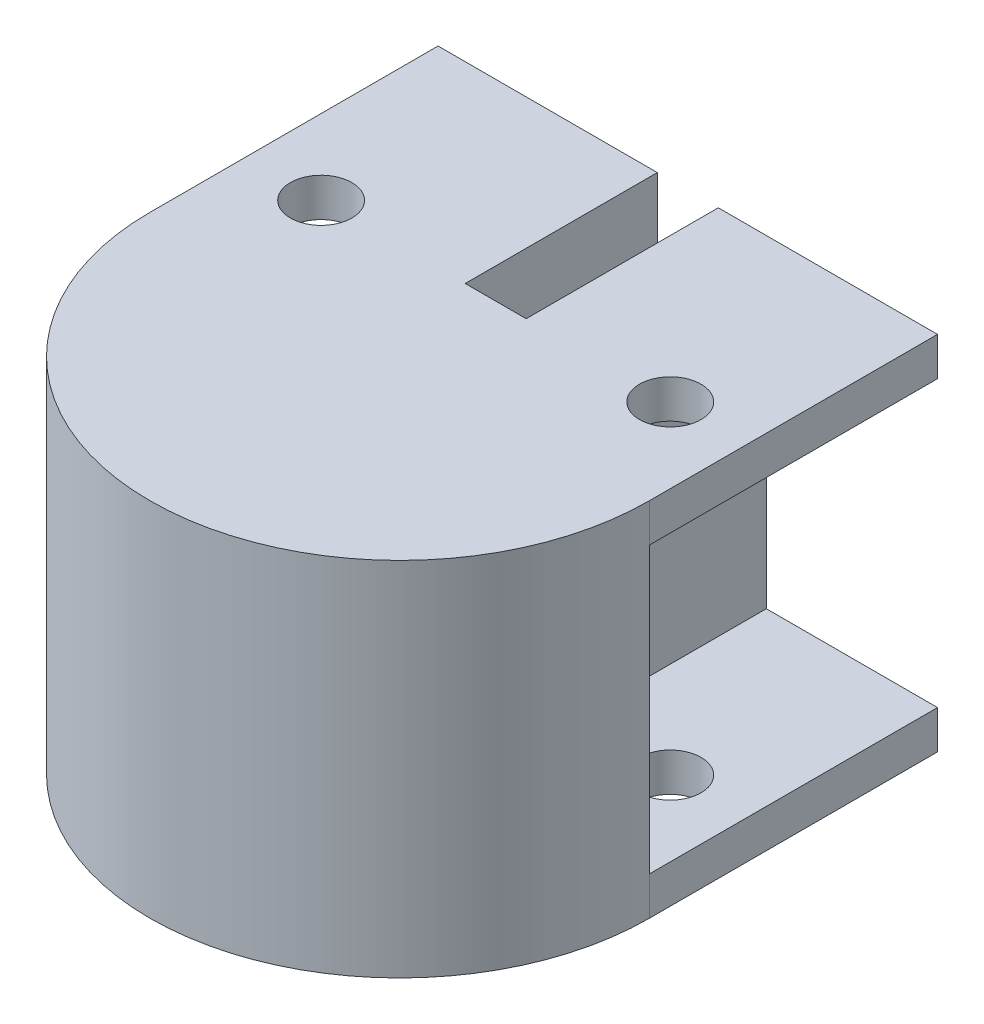
SolidWorks part; units mm, degrees
ref_plane "Front Plane" through (0, 0, 0) normal (0, 0, 1) x (1, 0, 0)
ref_plane "Top Plane" through (0, 0, 0) normal (0, 1, 0) x (1, 0, 0)
ref_plane "Right Plane" through (0, 0, 0) normal (1, 0, 0) x (0, 0, -1)
sketch "Sketch1" plane through (0, 0, 0) normal (0, 1, 0) x (1, 0, 0)
  line L0 (-1.5875, 0) -> (1.5875, 0)
  line L1 (1.5875, 0) -> (1.5875, 10)
  line L2 (1.5875, 10) -> (13, 10)
  line L3 (13, 10) -> (13, -5)
  line L4 (0, 0) -> (0, -18) construction
  line L5 (-13, 10) -> (-13, -5)
  line L6 (-1.5875, 10) -> (-13, 10)
  line L7 (-1.5875, 0) -> (-1.5875, 10)
  arc A0 (-13, -5) -> (13, -5) centre (0, -5) ccw
  circle A1 centre (9.0875, 0) radius 1.6
  circle A2 centre (-9.0875, 0) radius 1.6
  dimension "D5" = 3.2
  dimension "D1" = 1.5875
  dimension "D2" = 11.4125
  dimension "D3" = 15
  dimension "D4" = 10
  dimension "D6" = 7.5
extrude "Boss-Extrude1" add sketch "Sketch1" along normal blind 2
sketch "Sketch3" plane through (0, 0, 0) normal (0, -1, 0) x (1, 0, 0)
  line L0 (4.0875, -10) -> (1.5875, -10)
  line L1 (13, -10) -> (1.5875, -10) construction
  line L2 (1.5875, -10) -> (1.5875, 0)
  line L3 (1.5875, 0) -> (-1.5875, 0)
  line L4 (-1.5875, 0) -> (-1.5875, -10)
  line L5 (-1.5875, -10) -> (-4.0875, -10)
  line L6 (-1.5875, -10) -> (-13, -10) construction
  line L7 (-4.0875, -10) -> (-4.0875, 5)
  line L8 (-4.0875, 5) -> (-13, 5)
  line L9 (4.0875, -10) -> (4.0875, 5)
  line L10 (4.0875, 5) -> (13, 5)
  arc A0 (13, 5) -> (-13, 5) centre (0, 5) ccw
  dimension "D1" = 2.5
extrude "Boss-Extrude3" add sketch "Sketch3" along normal blind 7.4125
ref_plane "Plane2" through (0, -7.4125, 0) normal (0, -1, 0) x (-1, 0, 0)
mirror "Mirror11" about plane through (0, -7.4125, 0) normal (0, -1, 0) of "Boss-Extrude3"
mirror "Mirror12" about plane through (0, -7.4125, 0) normal (0, -1, 0) of "Boss-Extrude1"
